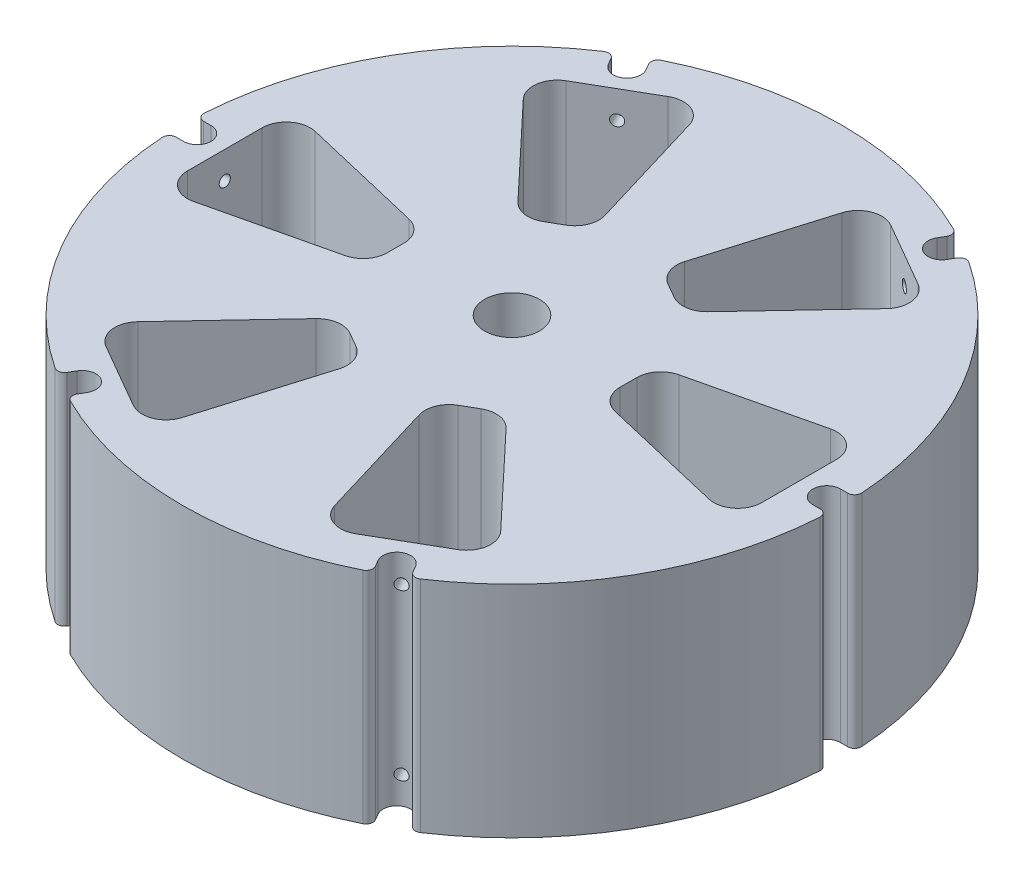
SolidWorks part; units mm, degrees
material "6061-T6 (SS)"
ref_plane "Front Plane" through (0, 0, 0) normal (0, 0, 1) x (1, 0, 0)
ref_plane "Top Plane" through (0, 0, 0) normal (0, 1, 0) x (1, 0, 0)
ref_plane "Right Plane" through (0, 0, 0) normal (1, 0, 0) x (0, 0, -1)
sketch "Sketch1" plane through (0, 0, 0) normal (0, 1, 0) x (1, 0, 0)
  circle A0 centre (0, 0) radius 76.2
  circle A1 centre (0, 0) radius 14.224
  dimension "D1" = 152.4
  dimension "D2" = 28.448
extrude "Boss-Extrude1" add sketch "Sketch1" against normal mid plane 50.8
sketch "Sketch3" plane through (0, -25.4, 0) normal (0, -1, 0) x (-1, 0, 0)
  line L0 (-76.1338, 3.175) -> (-72.771, 3.175)
  line L1 (-76.1338, -3.175) -> (-72.771, -3.175)
  circle A0 centre (0, 0) radius 76.2 construction
  arc A1 (-72.771, 3.175) -> (-72.771, -3.175) centre (-72.771, 0) cw
  arc A2 (-76.1338, -3.175) -> (-76.1338, 3.175) centre (0, 0) cw
  point P9 (-69.596, 0)
  point P13 (-76.2, 0)
  dimension "D1" = 6.35
  dimension "D2" = 6.604
extrude "Cut-Extrude1" cut sketch "Sketch3" against normal through all
sketch "Sketch4" plane through (0, -25.4, 0) normal (0, -1, 0) x (-1, 0, 0)
  line L0 (-66.421, 15.6653) -> (-66.421, -15.6653)
  line L1 (-66.421, -15.6653) -> (-26.924, -6.35)
  line L2 (-26.924, -6.35) -> (-26.924, 6.35)
  line L3 (-26.924, 6.35) -> (-66.421, 15.6653)
  line L4 (-66.421, 0) -> (0, 0) construction
  line L5 (-26.924, -6.35) -> (0, 0) construction
  circle A2 centre (0, 0) radius 14.224 construction
  point P12 (-14.224, 0)
  point P14 (-26.924, 0)
  dimension "D1" = 3.175
  dimension "D2" = 12.7
  dimension "D4" = 12.7
extrude "Cut-Extrude2" cut sketch "Sketch4" against normal through all
hole_wizard "#5-40 Tapped Hole1" positions "Sketch5" profile "Sketch6" tap size "#5-40" standard "ANSI Inch"
sketch "Sketch5" plane through (66.421, 0, 0) normal (-1, 0, 0) x (0, 0, 1)
  line L0 (-15.6653, -25.4) -> (15.6653, -25.4) construction
  point P0 (0, -19.05)
  dimension "D1" = 6.35
sketch "Sketch6" plane through (66.421, -19.05, 0) normal (0, 1, 0) x (0, 0, 1)
  line L0 (0, 0) -> (0, 9.7128)
  line L1 (0, 9.7128) -> (1.289, 9.7128)
  line L2 (1.289, 9.7128) -> (1.289, 0)
  line L5 (1.289, 0) -> (0, 0)
  line L11 (0, -6.35) -> (0, 107.95) construction
  dimension "Thru Tap Drill Dia." = 2.5781
  dimension "Thru Tap Drill Depth" = 9.7128
cosmetic thread "Hole Thread1" parameters "D2"=3.175
fillet "Fillet1" radius 1.5875 2 edges at (76.1338, 0, 3.175) (76.1338, 0, -3.175)
fillet "Fillet2" radius 5.5562 4 edges at (66.421, 0, 15.6653) (66.421, 0, -15.6653) (26.924, 0, 6.35) (26.924, 0, -6.35)
mirror "Mirror1" about plane through (0, 0, 0) normal (0, 1, 0) of "#5-40 Tapped Hole1"
cosmetic thread "Hole Thread7" parameters "D2"=3.175
pattern_circular "CirPattern1" count 6 over 360 about axis through (0, 0, 0) along (0, 1, 0) of "Cut-Extrude1", "Cut-Extrude2", "#5-40 Tapped Hole1", "Fillet1", "Fillet2", "Mirror1"
cosmetic thread "Hole Thread2" parameters "D2"=3.175
cosmetic thread "Hole Thread3" parameters "D2"=3.175
cosmetic thread "Hole Thread4" parameters "D2"=3.175
cosmetic thread "Hole Thread5" parameters "D2"=3.175
cosmetic thread "Hole Thread6" parameters "D2"=3.175
cosmetic thread "Hole Thread8" parameters "D2"=3.175
cosmetic thread "Hole Thread9" parameters "D2"=3.175
cosmetic thread "Hole Thread10" parameters "D2"=3.175
cosmetic thread "Hole Thread11" parameters "D2"=3.175
cosmetic thread "Hole Thread12" parameters "D2"=3.175
sketch "Sketch7" plane through (0, 25.4, 0) normal (0, 1, 0) x (1, 0, 0)
  circle A0 centre (0, 0) radius 6.35
  circle A1 centre (0, 0) radius 14.224
  circle A2 centre (0, 0) radius 14.224 construction
  dimension "D1" = 12.7
extrude "Boss-Extrude2" add sketch "Sketch7" against normal offset from surface (23.368 mm away) 27.432 up to face at (23.0633, -25.4, 39.9469)
